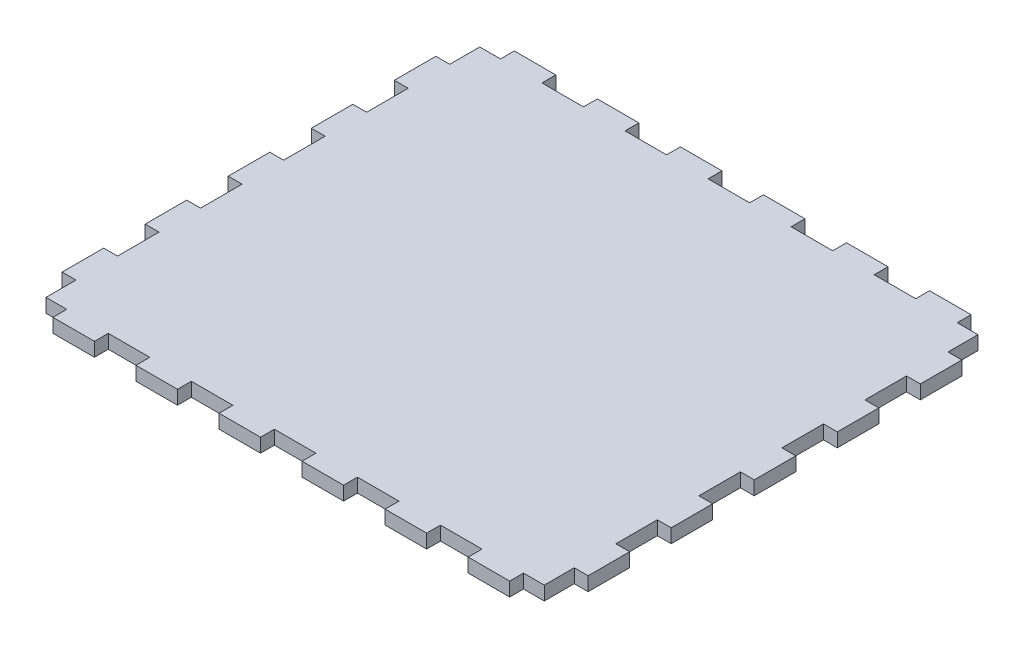
SolidWorks part; units mm, degrees
ref_plane "Front Plane" through (0, 0, 0) normal (0, 0, 1) x (1, 0, 0)
ref_plane "Top Plane" through (0, 0, 0) normal (0, 1, 0) x (1, 0, 0)
ref_plane "Right Plane" through (0, 0, 0) normal (1, 0, 0) x (0, 0, -1)
sketch "Sketch1" plane through (0, 0, 0) normal (0, 1, 0) x (1, 0, 0)
  line L97 (49.5, 50) -> (40.5, 50)
  line L98 (40.5, 50) -> (40.5, 47)
  line L99 (40.5, 47) -> (31.5, 47)
  line L100 (31.5, 47) -> (31.5, 50)
  line L101 (31.5, 50) -> (22.5, 50)
  line L102 (22.5, 50) -> (22.5, 47)
  line L103 (22.5, 47) -> (13.5, 47)
  line L104 (13.5, 47) -> (13.5, 50)
  line L105 (13.5, 50) -> (4.5, 50)
  line L106 (4.5, 50) -> (4.5, 47)
  line L107 (4.5, 47) -> (-4.5, 47)
  line L108 (-4.5, 47) -> (-4.5, 50)
  line L109 (-4.5, 50) -> (-13.5, 50)
  line L110 (-13.5, 50) -> (-13.5, 47)
  line L111 (-13.5, 47) -> (-22.5, 47)
  line L112 (-22.5, 47) -> (-22.5, 50)
  line L113 (-22.5, 50) -> (-31.5, 50)
  line L114 (-31.5, 50) -> (-31.5, 47)
  line L115 (-31.5, 47) -> (-40.5, 47)
  line L116 (-40.5, 47) -> (-40.5, 50)
  line L117 (-40.5, 50) -> (-49.5, 50)
  line L118 (-49.5, 50) -> (-49.5, 47)
  line L119 (-49.5, 47) -> (-54, 47)
  line L120 (-54, 47) -> (-54, 40.5)
  line L121 (-54, 40.5) -> (-57, 40.5)
  line L122 (-57, 40.5) -> (-57, 31.5)
  line L123 (-57, 31.5) -> (-54, 31.5)
  line L124 (-54, 31.5) -> (-54, 22.5)
  line L125 (-54, 22.5) -> (-57, 22.5)
  line L126 (-57, 22.5) -> (-57, 13.5)
  line L127 (-57, 13.5) -> (-54, 13.5)
  line L128 (-54, 13.5) -> (-54, 4.5)
  line L129 (-54, 4.5) -> (-57, 4.5)
  line L130 (-57, 4.5) -> (-57, -4.5)
  line L131 (-57, -4.5) -> (-54, -4.5)
  line L132 (-54, -4.5) -> (-54, -13.5)
  line L133 (-54, -13.5) -> (-57, -13.5)
  line L134 (-57, -13.5) -> (-57, -22.5)
  line L135 (-57, -22.5) -> (-54, -22.5)
  line L136 (-54, -22.5) -> (-54, -31.5)
  line L137 (-54, -31.5) -> (-57, -31.5)
  line L138 (-57, -31.5) -> (-57, -40.5)
  line L139 (-57, -40.5) -> (-54, -40.5)
  line L140 (-54, -40.5) -> (-54, -47)
  line L141 (-54, -47) -> (-49.5, -47)
  line L142 (-49.5, -47) -> (-49.5, -50)
  line L143 (-49.5, -50) -> (-40.5, -50)
  line L144 (-40.5, -50) -> (-40.5, -47)
  line L145 (-40.5, -47) -> (-31.5, -47)
  line L146 (-31.5, -47) -> (-31.5, -50)
  line L147 (-31.5, -50) -> (-22.5, -50)
  line L148 (-22.5, -50) -> (-22.5, -47)
  line L149 (-22.5, -47) -> (-13.5, -47)
  line L150 (-13.5, -47) -> (-13.5, -50)
  line L151 (-13.5, -50) -> (-4.5, -50)
  line L152 (-4.5, -50) -> (-4.5, -47)
  line L153 (-4.5, -47) -> (4.5, -47)
  line L154 (4.5, -47) -> (4.5, -50)
  line L155 (4.5, -50) -> (13.5, -50)
  line L156 (13.5, -50) -> (13.5, -47)
  line L157 (13.5, -47) -> (22.5, -47)
  line L158 (22.5, -47) -> (22.5, -50)
  line L159 (22.5, -50) -> (31.5, -50)
  line L160 (31.5, -50) -> (31.5, -47)
  line L161 (31.5, -47) -> (40.5, -47)
  line L162 (40.5, -47) -> (40.5, -50)
  line L163 (40.5, -50) -> (49.5, -50)
  line L164 (49.5, -50) -> (49.5, -47)
  line L165 (49.5, -47) -> (54, -47)
  line L166 (54, -47) -> (54, -40.5)
  line L167 (54, -40.5) -> (57, -40.5)
  line L168 (57, -40.5) -> (57, -31.5)
  line L169 (57, -31.5) -> (54, -31.5)
  line L170 (54, -31.5) -> (54, -22.5)
  line L171 (54, -22.5) -> (57, -22.5)
  line L172 (57, -22.5) -> (57, -13.5)
  line L173 (57, -13.5) -> (54, -13.5)
  line L174 (54, -13.5) -> (54, -4.5)
  line L175 (54, -4.5) -> (57, -4.5)
  line L176 (57, -4.5) -> (57, 4.5)
  line L177 (57, 4.5) -> (54, 4.5)
  line L178 (54, 4.5) -> (54, 13.5)
  line L179 (54, 13.5) -> (57, 13.5)
  line L180 (57, 13.5) -> (57, 22.5)
  line L181 (57, 22.5) -> (54, 22.5)
  line L182 (54, 22.5) -> (54, 31.5)
  line L183 (54, 31.5) -> (57, 31.5)
  line L184 (57, 31.5) -> (57, 40.5)
  line L185 (57, 40.5) -> (54, 40.5)
  line L186 (54, 40.5) -> (54, 47)
  line L187 (54, 47) -> (49.5, 47)
  line L188 (49.5, 47) -> (49.5, 50)
  line L189 (-57, 40.5) -> (-57, 50) construction
  line L190 (-57, 50) -> (-49.5, 50) construction
  line L191 (57, -40.5) -> (57, -50) construction
  line L192 (57, -50) -> (49.5, -50) construction
  line L193 (-57, 50) -> (57, -50) construction
  point P0 (0, 0)
extrude "Boss-Extrude1" add sketch "Sketch1" along normal mid plane 3
sketch "Sketch2" plane through (0, 1.5, 0) normal (0, 1, 0) x (1, 0, 0)
  text T0 "Top/Bottom"
extrude "Cut-Extrude1" [suppressed] cut sketch "Sketch2" against normal blind 1
